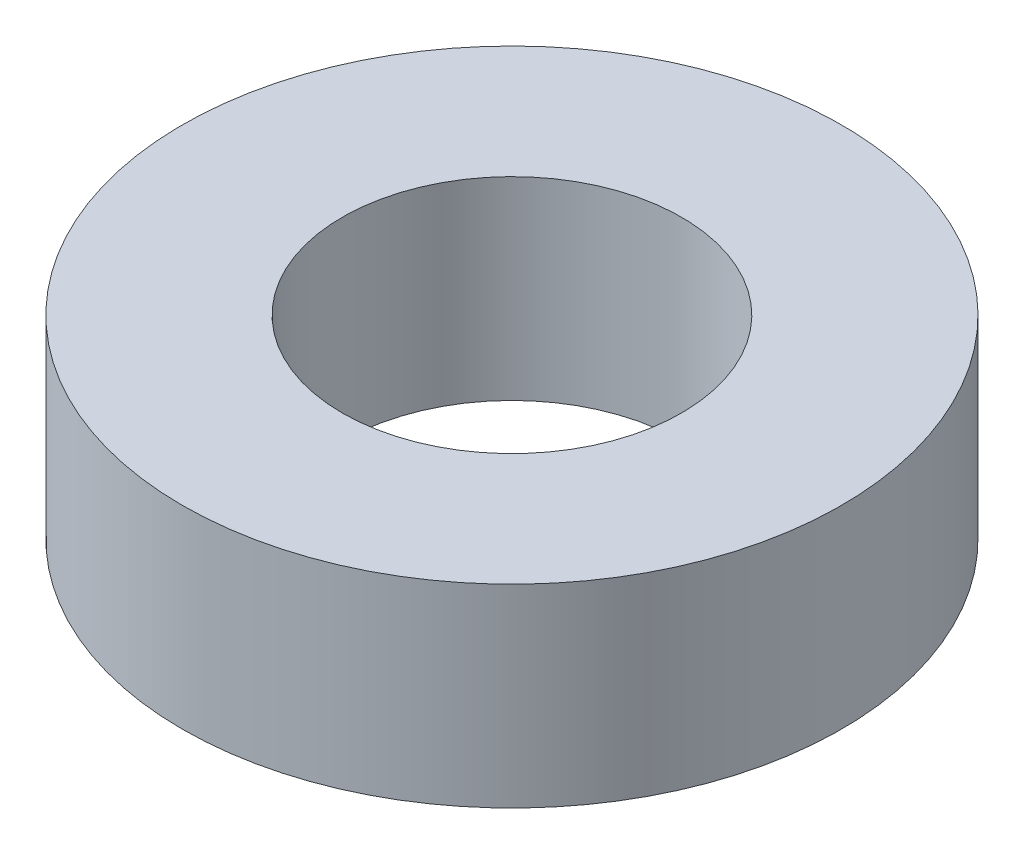
SolidWorks part; units mm, degrees
ref_plane "Front Plane" through (0, 0, 0) normal (0, 0, 1) x (1, 0, 0)
ref_plane "Top Plane" through (0, 0, 0) normal (0, 1, 0) x (1, 0, 0)
ref_plane "Right Plane" through (0, 0, 0) normal (1, 0, 0) x (0, 0, -1)
sketch "Sketch1" plane through (0, 0, 0) normal (0, 1, 0) x (1, 0, 0)
  circle A0 centre (0, 0) radius 4.375
  circle A1 centre (0, 0) radius 8.5
  dimension "D1" = 17
  dimension "D2" = 8.75
extrude "Boss-Extrude1" add sketch "Sketch1" along normal blind 5 contours A1
